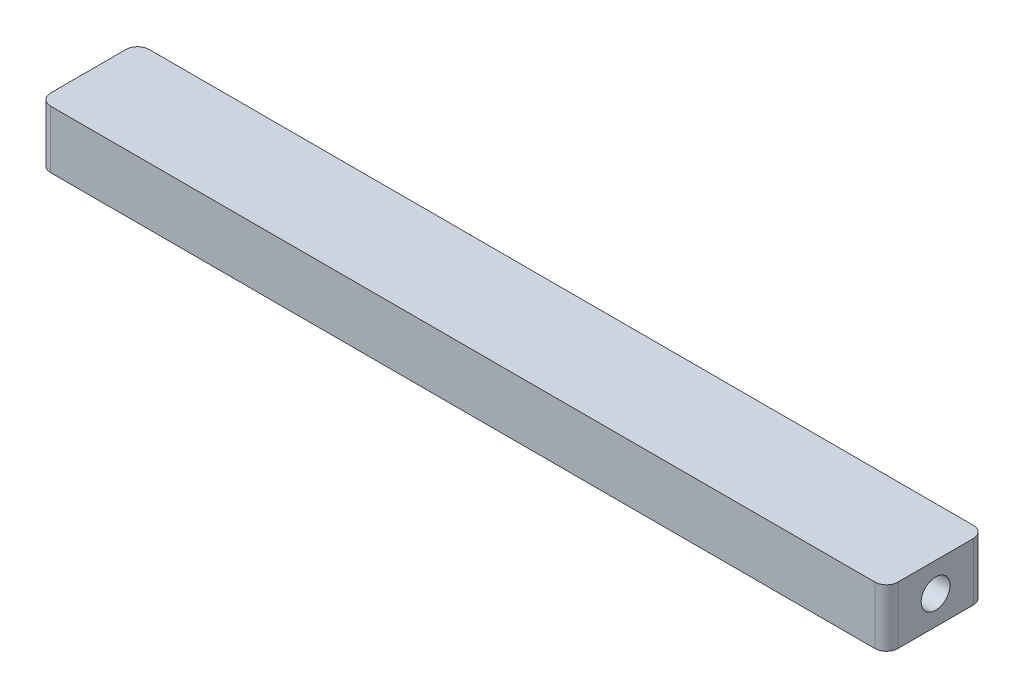
SolidWorks part; units mm, degrees
ref_plane "Ön Düzlem" through (0, 0, 0) normal (0, 0, 1) x (1, 0, 0)
ref_plane "Üst Düzlem" through (0, 0, 0) normal (0, 1, 0) x (1, 0, 0)
ref_plane "Sağ Düzlem" through (0, 0, 0) normal (1, 0, 0) x (0, 0, -1)
sketch "Çizim1" plane through (0, 0, 0) normal (0, 1, 0) x (1, 0, 0)
  line L4 (-48.7697, 34.2251) -> (94.3013, 34.2251)
  line L7 (96.3013, 32.2251) -> (96.3013, 19.1541)
  line L8 (94.3013, 17.1541) -> (-48.7697, 17.1541)
  line L9 (-50.7697, 19.1541) -> (-50.7697, 32.2251)
  arc A2 (96.3013, 32.2251) -> (94.3013, 34.2251) centre (94.3013, 32.2251) ccw
  arc A3 (96.3013, 19.1541) -> (94.3013, 17.1541) centre (94.3013, 19.1541) cw
  arc A4 (-50.7697, 19.1541) -> (-48.7697, 17.1541) centre (-48.7697, 19.1541) ccw
  arc A5 (-50.7697, 32.2251) -> (-48.7697, 34.2251) centre (-48.7697, 32.2251) cw
  point P0 (0, 0)
  dimension "D1" = 2
extrude "Yükseklik-Ekstrüzyon1" add sketch "Çizim1" along normal blind 10
sketch "Çizim2" plane through (96.3013, 0, 0) normal (1, 0, 0) x (0, 0, -1)
  circle A0 centre (25.6896, 5) radius 2.5
extrude "Kes-Ekstrüzyon1" cut sketch "Çizim2" against normal blind 170
